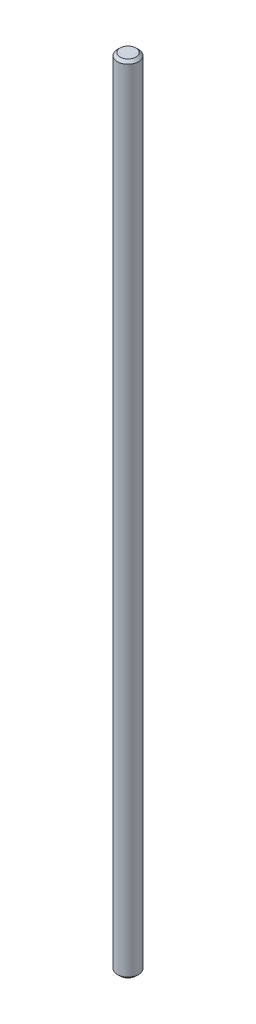
SolidWorks part; units mm, degrees
ref_plane "Front Plane" through (0, 0, 0) normal (0, 0, 1) x (1, 0, 0)
ref_plane "Top Plane" through (0, 0, 0) normal (0, 1, 0) x (1, 0, 0)
ref_plane "Right Plane" through (0, 0, 0) normal (1, 0, 0) x (0, 0, -1)
sketch "Sketch1" plane through (0, 0, 0) normal (0, 1, 0) x (1, 0, 0)
  circle A0 centre (0, 0) radius 4
  dimension "D1" = 8
extrude "Boss-Extrude1" add sketch "Sketch1" along normal blind 300
chamfer "Chamfer1" distance 1 angle 45 2 edges at (0, 0, 4) (0, 300, 4)
